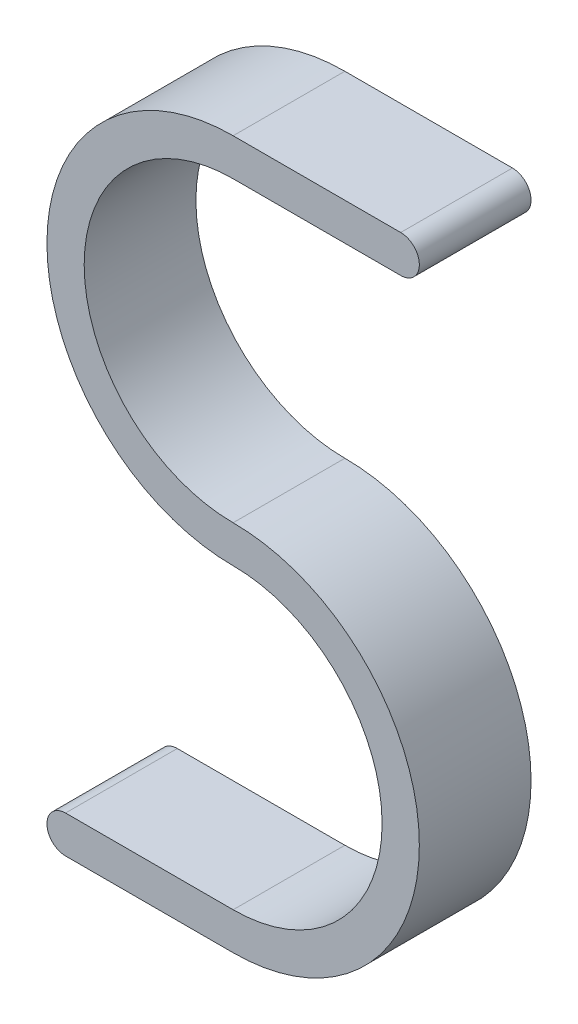
SolidWorks part; units mm, degrees
ref_plane "Front Plane" through (0, 0, 0) normal (0, 0, 1) x (1, 0, 0)
ref_plane "Top Plane" through (0, 0, 0) normal (0, 1, 0) x (1, 0, 0)
ref_plane "Right Plane" through (0, 0, 0) normal (1, 0, 0) x (0, 0, -1)
sketch "Sketch2" plane through (0, 0, 0) normal (0, 0, 1) x (1, 0, 0)
  line L0 (-43.7625, 0) -> (50.3522, 0) construction
  line L2 (-0.8289, 40) -> (21.6712, 40)
  line L4 (21.6711, 45) -> (-0.8289, 45)
  line L5 (-23.3289, -50) -> (-0.8289, -50)
  line L6 (-0.8289, -45) -> (-23.3289, -45)
  arc A3 (21.6712, 40) -> (21.6711, 45) centre (21.6712, 42.5) ccw
  arc A5 (-0.8289, 40) -> (-0.8289, 0) centre (-0.8289, 20) ccw
  arc A6 (-0.8289, 45) -> (-0.8289, -5) centre (-0.8289, 20) ccw
  arc A7 (-0.8289, -45) -> (-0.8289, -5) centre (-0.8289, -25) ccw
  arc A8 (-0.8289, -50) -> (-0.8289, 0) centre (-0.8289, -25) ccw
  arc A9 (-23.3289, -45) -> (-23.3289, -50) centre (-23.3289, -47.5) ccw
  point P8 (-0.8289, -61.8107)
  dimension "D1" = 5
  dimension "D2" = 40
  dimension "D4" = 2.5
  dimension "D5" = 40
  dimension "D6" = 2
  dimension "D3" = 22.5
  dimension "D7" = 50
extrude "Boss-Extrude1" add sketch "Sketch2" along normal blind 15
